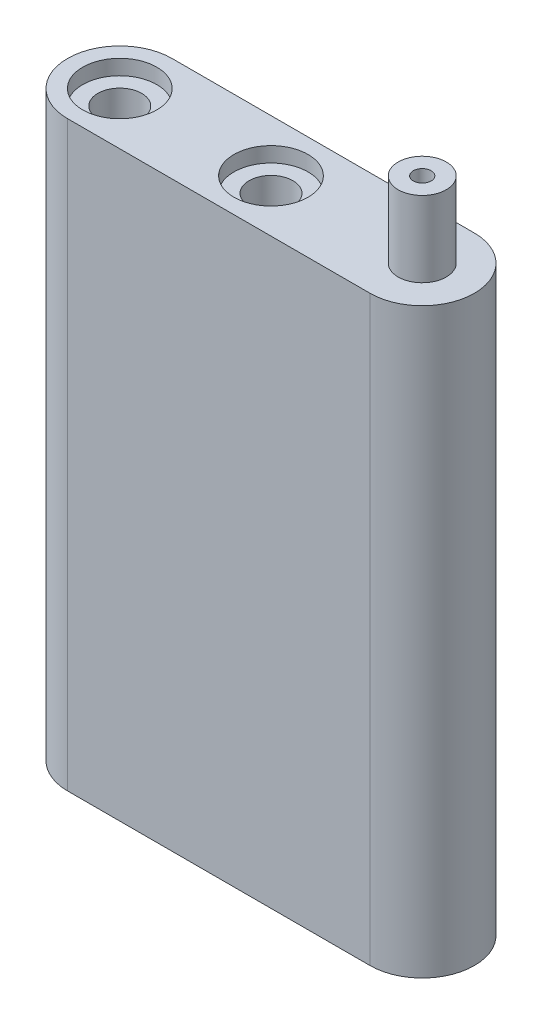
SolidWorks part; units mm, degrees
ref_plane "Alzado" through (0, 0, 0) normal (0, 0, 1) x (1, 0, 0)
ref_plane "Planta" through (0, 0, 0) normal (0, 1, 0) x (1, 0, 0)
ref_plane "Vista lateral" through (0, 0, 0) normal (1, 0, 0) x (0, 0, -1)
sketch "Croquis2" plane through (0, 0, 0) normal (0, 1, 0) x (1, 0, 0)
  line L0 (0, 3.45) -> (20, 3.45)
  line L1 (0, -3.45) -> (20, -3.45)
  circle A0 centre (0, 0) radius 1.45
  circle A1 centre (10, 0) radius 1.45
  circle A2 centre (20, 0) radius 1.45 construction
  arc A3 (0, 3.45) -> (0, -3.45) centre (0, 0) ccw
  arc A4 (20, -3.45) -> (20, 3.45) centre (20, 0) ccw
  circle A6 centre (0, 0) radius 3.45 construction
  circle A7 centre (20, 0) radius 3.45 construction
  point P8 (23.2993, 1.0087)
  point P15 (3.45, 0)
  dimension "D1" = 2.9
  dimension "D2" = 2.9
  dimension "D3" = 2.9
  dimension "D5" = 10
  dimension "D4" = 10
  dimension "D6" = 2
extrude "Saliente-Extruir1" add sketch "Croquis2" along normal blind 2.5
sketch "Croquis4" plane through (0, 2.5, 0) normal (0, 1, 0) x (1, 0, 0)
  circle A7 centre (0, 0) radius 2.45
  circle A8 centre (0, 0) radius 2.45
  circle A10 centre (10, 0) radius 2.45
  circle A11 centre (10, 0) radius 2.45
  dimension "D1" = 1
  dimension "D2" = 1
extrude "Cortar-Extruir1" cut sketch "Croquis4" against normal blind 1
sketch "Croquis5" plane through (0, 2.5, 0) normal (0, 1, 0) x (1, 0, 0)
  circle A0 centre (20, 0) radius 1.59
  circle A1 centre (20, 0) radius 0.59
  dimension "D1" = 3.18
  dimension "D2" = 1
extrude "Saliente-Extruir2" add sketch "Croquis5" along normal blind 5
sketch "Croquis6" plane through (0, 2.5, 0) normal (0, 1, 0) x (1, 0, 0)
  circle A0 centre (20, 0) radius 0.475
extrude "Cortar-Extruir2" cut sketch "Croquis6" against normal through all
sketch "Croquis7" plane through (0, 0, 0) normal (0, -1, 0) x (1, 0, 0)
  line L2 (0, -3.45) -> (20, -3.45)
  line L3 (20, 3.45) -> (0, 3.45)
  line L4 (0, -3.45) -> (20, -3.45)
  line L5 (20, 3.45) -> (0, 3.45)
  circle A0 centre (0, 0) radius 1.45 construction
  circle A1 centre (10, 0) radius 1.45 construction
  arc A2 (0, 3.45) -> (0, -3.45) centre (0, 0) ccw
  arc A3 (20, -3.45) -> (20, 3.45) centre (20, 0) ccw
  arc A4 (0, 3.45) -> (0, -3.45) centre (0, 0) ccw
  arc A5 (20, -3.45) -> (20, 3.45) centre (20, 0) ccw
  circle A6 centre (0, 0) radius 1.45
  circle A7 centre (10, 0) radius 1.45
  dimension "D1" = 0
extrude "Saliente-Extruir3" add sketch "Croquis7" along normal blind 36
